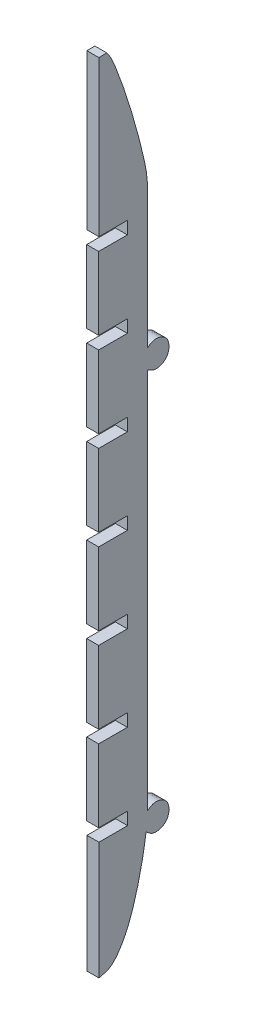
SolidWorks part; units mm, degrees
ref_plane "Alzado" through (0, 0, 0) normal (1, 0, 0) x (0, 1, 0)
ref_plane "Planta" through (0, 0, 0) normal (0, 0, 1) x (0, 1, 0)
ref_plane "Vista lateral" through (0, 0, 0) normal (0, 1, 0) x (-1, 0, 0)
sketch "Croquis1" plane through (0, 0, 0) normal (1, 0, 0) x (0, 1, 0)
  line L0 (-22.1106, -6.419) -> (-19.2606, -6.419)
  line L2 (-60.6319, -6.4784) -> (-57.7819, -6.4784)
  line L3 (-57.7819, -6.4784) -> (-57.7819, 0.0595)
  line L4 (-57.7819, 0.0595) -> (-41.3713, 0.0595)
  line L5 (-41.3713, 0.0595) -> (-41.3713, -6.419)
  line L6 (-41.3713, -6.419) -> (-38.5213, -6.419)
  line L7 (-38.5213, -6.419) -> (-38.5213, 0.0595)
  line L8 (-38.5213, 0.0595) -> (-22.1106, 0.0595)
  line L9 (-22.1106, 0.0595) -> (-22.1106, -6.419)
  line L10 (-19.2606, -6.419) -> (-19.2606, 0.0595)
  line L11 (-19.2606, 0.0595) -> (-2.8499, 0.0595)
  line L12 (-2.8499, 0.0595) -> (-2.8499, -6.419)
  line L13 (-2.8499, -6.419) -> (0.0001, -6.419)
  line L14 (0.0001, -6.419) -> (0.0001, 0.0595)
  line L15 (0.0001, 0.0595) -> (16.4107, 0.0595)
  line L16 (16.4107, 0.0595) -> (16.4107, -6.419)
  line L17 (16.4107, -6.419) -> (19.2607, -6.419)
  line L18 (19.2607, -6.419) -> (19.2607, 0.0595)
  line L19 (19.2607, 0.0595) -> (35.6713, 0.0595)
  line L20 (35.6713, 0.0595) -> (35.6713, -6.419)
  line L21 (35.6713, -6.419) -> (38.5213, -6.419)
  line L22 (38.5213, -6.419) -> (38.5213, 0.0595)
  line L23 (38.5213, 0.0595) -> (54.932, 0.0595)
  line L24 (54.932, 0.0595) -> (54.932, -6.419)
  line L25 (54.932, -6.419) -> (57.782, -6.419)
  line L26 (57.782, -6.419) -> (57.782, 0)
  line L27 (57.782, 0) -> (92.812, 0)
  line L28 (92.812, 0) -> (92.8401, -1.7851)
  line L29 (62.8243, -10.9405) -> (30.5943, -10.9405)
  line L30 (26.2873, -10.9405) -> (-59.9512, -10.9405)
  line L31 (-87.188, 0) -> (-60.6319, 0)
  line L32 (-60.6319, 0) -> (-60.6319, -6.4784)
  spline S0 degree 3 poles (92.8401, -1.7851) (92.4472, -2.0647) (91.5621, -2.6945) (89.2139, -3.7003) (84.2493, -5.6173) (76.7499, -7.958) (69.6817, -9.8204) (65.0659, -10.7728) (63.4815, -10.8914) (62.8243, -10.9405) knots 0 0 0 0 0.04574 0.103061 0.241854 0.552586 0.84901 0.937364 1 1 1 1
  spline S1 degree 3 poles (30.5943, -10.9405) (30.9214, -11.4421) (31.5555, -12.4144) (31.2682, -14.1732) (30.1824, -15.5925) (29.0345, -15.7914) (28.4408, -15.8943) knots 0 0 0 0 0.257584 0.499276 0.740986 1 1 1 1
  spline S2 degree 3 poles (28.4408, -15.8943) (27.847, -15.7914) (26.6992, -15.5925) (25.6134, -14.1732) (25.3261, -12.4144) (25.9602, -11.4421) (26.2873, -10.9405) knots 0 0 0 0 0.259011 0.50072 0.742413 1 1 1 1
  spline S3 degree 3 poles (-59.9512, -10.9405) (-59.6241, -11.4421) (-58.99, -12.4144) (-59.2773, -14.1732) (-60.3631, -15.5925) (-61.5109, -15.7914) (-62.1047, -15.8943) knots 0 0 0 0 0.257587 0.499281 0.740991 1 1 1 1
  spline S4 degree 3 poles (-62.1047, -15.8943) (-62.7377, -15.7776) (-63.9582, -15.5527) (-65.0269, -13.9718) (-65.1729, -12.0727) (-64.3637, -11.1352) (-63.9446, -10.6498) knots 0 0 0 0 0.2595 0.500354 0.741301 1 1 1 1
  spline S5 degree 3 poles (-63.9446, -10.6498) (-65.1243, -10.4682) (-67.9233, -10.0375) (-72.4708, -9.094) (-78.2125, -7.5205) (-83.096, -5.5276) (-86.6008, -2.6673) (-87.0028, -0.8413) (-87.188, 0) knots 0 0 0 0 0.133262 0.316184 0.518474 0.796547 0.906269 1 1 1 1
  point P0 (0, 0)
  point P1 (-57.8624, -34.3078)
  dimension "D1" = 2.85
  dimension "D2" = 2.85
  dimension "D3" = 2.85
  dimension "D4" = 2.85
  dimension "D5" = 2.85
  dimension "D6" = 2.85
  dimension "D7" = 2.85
  dimension "D8" = 180
  dimension "D9" = 11
  dimension "D10" = 11
  dimension "D11" = 11
  dimension "D12" = 11
  dimension "D13" = 11
extrude "Saliente-Extruir1" add sketch "Croquis1" along normal blind 2.7
